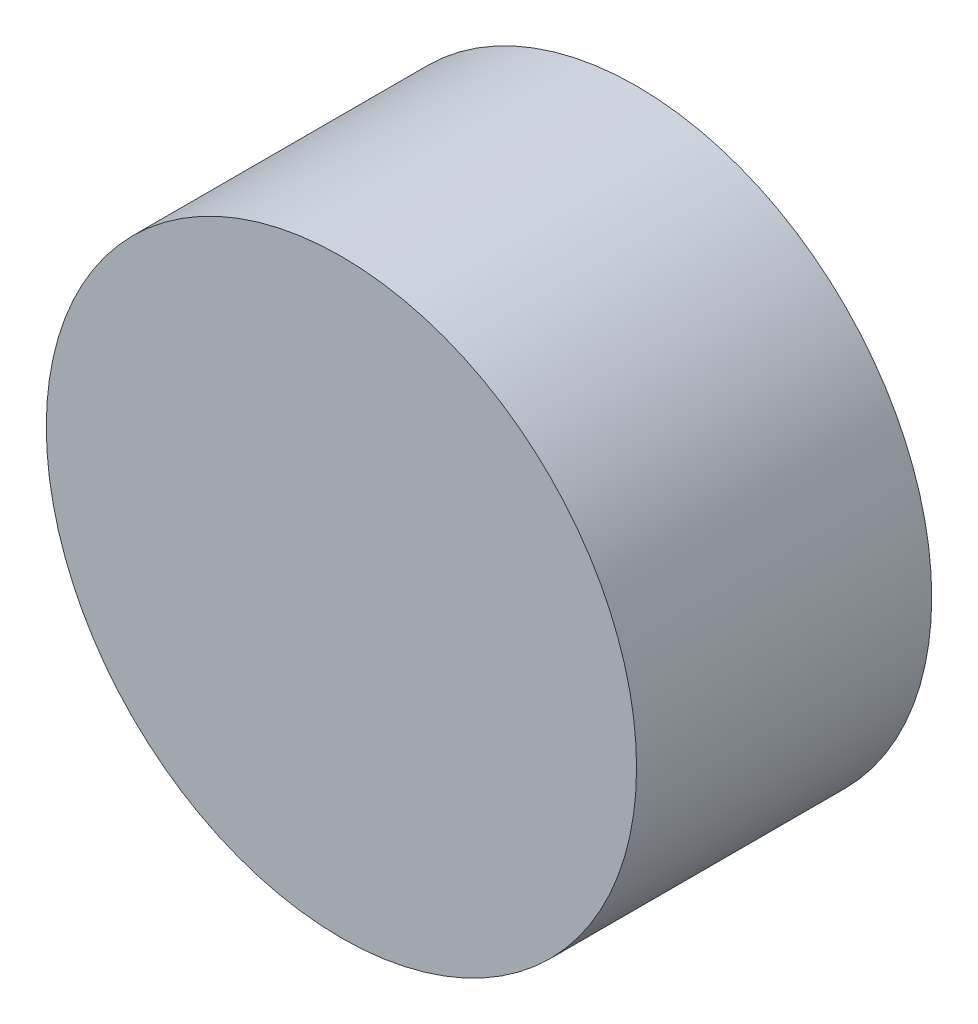
SolidWorks part; units mm, degrees
ref_plane "Front Plane" through (0, 0, 0) normal (0, 0, 1) x (1, 0, 0)
ref_plane "Top Plane" through (0, 0, 0) normal (0, 1, 0) x (1, 0, 0)
ref_plane "Right Plane" through (0, 0, 0) normal (1, 0, 0) x (0, 0, -1)
sketch "Sketch1" plane through (0, 0, 0) normal (0, 0, 1) x (1, 0, 0)
  circle A0 centre (0, 0) radius 5
  dimension "D1" = 10
extrude "Boss-Extrude1" add sketch "Sketch1" along normal blind 5
sketch "Sketch2" plane through (0, 0, 0) normal (0, 1, 0) x (1, 0, 0)
  line L0 (0, 0) -> (0, 1.5) construction
  line L1 (-1.25, 0) -> (1.25, 0)
  line L3 (5, 0) -> (-5, 0) construction
  line L4 (1.25, 0) -> (1.25, 1.5)
  line L5 (-1.25, 1.5) -> (-1.25, 0)
  arc A0 (1.25, 1.5) -> (-1.25, 1.5) centre (0, 1.5) ccw
  circle A1 centre (0, 1.5) radius 0.5
  point P10 (0, 0)
  dimension "D2" = 2.5
  dimension "D3" = 1
  dimension "D1" = 1.5
extrude "Boss-Extrude2" add sketch "Sketch2" along normal mid plane 2
